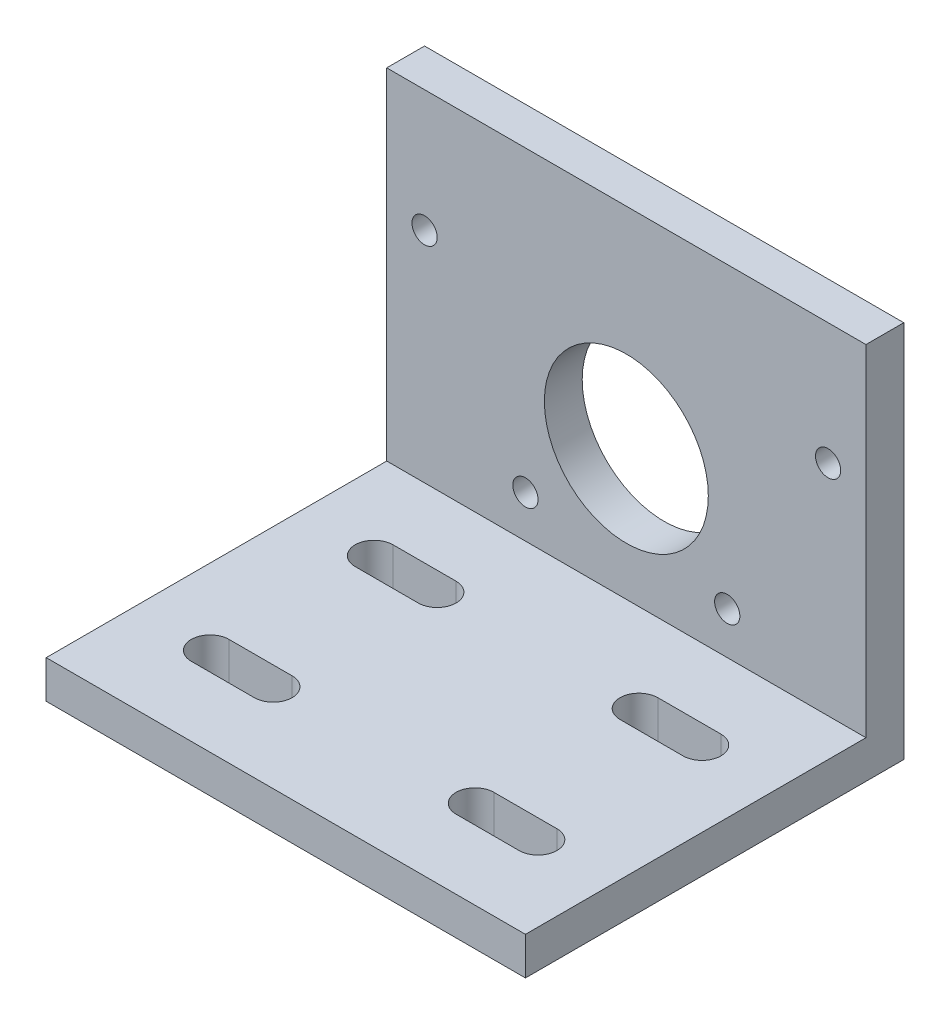
SolidWorks part; units mm, degrees
ref_plane "Front Plane" through (0, 0, 0) normal (0, 0, 1) x (1, 0, 0)
ref_plane "Top Plane" through (0, 0, 0) normal (0, 1, 0) x (1, 0, 0)
ref_plane "Right Plane" through (0, 0, 0) normal (1, 0, 0) x (0, 0, -1)
sketch "Sketch2" plane through (0, 0, 0) normal (0, 1, 0) x (1, 0, 0)
  line L1 (-19, 15) -> (19, 15)
  line L2 (-19, 15) -> (-19, -15)
  line L3 (-19, -15) -> (19, -15)
  line L4 (19, 15) -> (19, -15)
  line L5 (-19, 15) -> (19, -15) construction
  line L6 (-19, -15) -> (19, 15) construction
  point P0 (0, 0)
  dimension "D1" = 38
  dimension "D2" = 30
extrude "Boss-Extrude1" add sketch "Sketch2" along normal blind 3
sketch "Sketch3" plane through (0, 3, 0) normal (0, 1, 0) x (1, 0, 0)
  line L0 (19, -15) -> (19, 15) construction
  line L1 (-19, 15) -> (19, 15)
  line L2 (-19, 15) -> (-19, 12)
  line L3 (-19, 12) -> (19, 12)
  line L4 (19, 15) -> (19, 12)
  dimension "D1" = 3
extrude "Boss-Extrude2" add sketch "Sketch3" along normal blind 27
sketch "Sketch4" plane through (0, 0, -12) normal (0, 0, 1) x (1, 0, 0)
  line L0 (-19, 0) -> (19, 0) construction
  circle A0 centre (0, 13.35) radius 6.5
  dimension "D1" = 13
  dimension "D2" = 13.35
extrude "Cut-Extrude1" cut sketch "Sketch4" against normal blind 27
sketch "Sketch5" plane through (0, 3, 0) normal (0, 1, 0) x (1, 0, 0)
  line L0 (-13, 5) -> (-8, 5) construction
  line L1 (-13, 6.5) -> (-8, 6.5)
  line L2 (-13, 3.5) -> (-8, 3.5)
  line L3 (8, 5) -> (13, 5) construction
  line L4 (8, 6.5) -> (13, 6.5)
  line L5 (8, 3.5) -> (13, 3.5)
  line L6 (8, -8) -> (13, -8) construction
  line L7 (8, -6.5) -> (13, -6.5)
  line L8 (8, -9.5) -> (13, -9.5)
  line L9 (-13, -8) -> (-8, -8) construction
  line L10 (-13, -6.5) -> (-8, -6.5)
  line L11 (-13, -9.5) -> (-8, -9.5)
  line L12 (19, -15) -> (19, 12) construction
  line L13 (-19, 12) -> (-19, -15) construction
  line L14 (-19, 12) -> (19, 12) construction
  line L15 (-19, -15) -> (19, -15) construction
  arc A0 (-13, 6.5) -> (-13, 3.5) centre (-13, 5) ccw
  arc A1 (-8, 3.5) -> (-8, 6.5) centre (-8, 5) ccw
  arc A2 (8, 6.5) -> (8, 3.5) centre (8, 5) ccw
  arc A3 (13, 3.5) -> (13, 6.5) centre (13, 5) ccw
  arc A4 (8, -6.5) -> (8, -9.5) centre (8, -8) ccw
  arc A5 (13, -9.5) -> (13, -6.5) centre (13, -8) ccw
  arc A6 (-13, -6.5) -> (-13, -9.5) centre (-13, -8) ccw
  arc A7 (-8, -9.5) -> (-8, -6.5) centre (-8, -8) ccw
  point P2 (-10.5, 5)
  point P7 (10.5, 5)
  point P16 (10.5, -8)
  point P21 (-10.5, -8)
  point P32 (0, 0)
  point P33 (0, 0)
  point P34 (0, 0)
  point P35 (0, 0)
  point P36 (0, 0)
  point P39 (0, 0)
  dimension "D3" = 1.5
  dimension "D7" = 1.5
  dimension "D9" = 1.5
  dimension "D10" = 1.5
  dimension "D1" = 6
  dimension "D2" = 6
  dimension "D4" = 7
  dimension "D5" = 5
  dimension "D6" = 5
  dimension "D8" = 7
extrude "Cut-Extrude2" cut sketch "Sketch5" against normal through all
sketch "Sketch6" plane through (0, 0, -12) normal (0, 0, 1) x (1, 0, 0)
  circle A0 centre (16, 20.35) radius 1
  circle A1 centre (-16, 20.35) radius 1
  circle A2 centre (-8, 6.35) radius 1
  circle A3 centre (8, 6.35) radius 1
  circle A4 centre (0, 13.35) radius 6.5 construction
  dimension "D4" = 2
  dimension "D5" = 2
  dimension "D11" = 2
  dimension "D12" = 2
  dimension "D1" = 16
  dimension "D2" = 8
  dimension "D3" = 8
  dimension "D6" = 7
  dimension "D7" = 32
  dimension "D8" = 16
  dimension "D9" = 16
  dimension "D10" = 7
extrude "Cut-Extrude3" cut sketch "Sketch6" against normal through all
